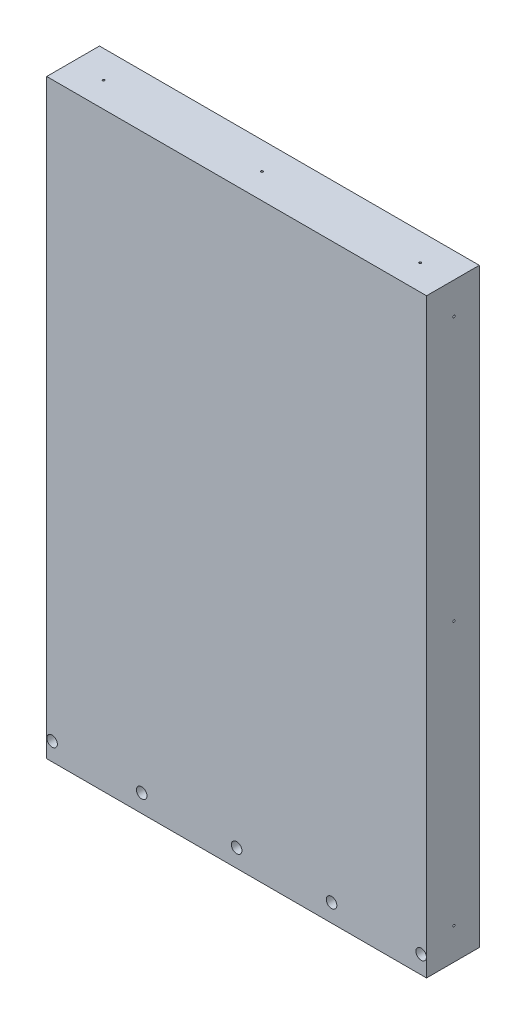
SolidWorks part; units mm, degrees
material "Cedro"
ref_plane "Plano frontal" through (0, 0, 0) normal (0, 0, 1) x (1, 0, 0)
ref_plane "Plano superior" through (0, 0, 0) normal (0, 1, 0) x (1, 0, 0)
ref_plane "Plano direito" through (0, 0, 0) normal (1, 0, 0) x (0, 0, -1)
sketch "Esboço1" plane through (0, 0, 0) normal (0, 0, 1) x (1, 0, 0)
  line L1 (0, 0) -> (180, 0)
  line L2 (0, 0) -> (0, 280)
  line L3 (0, 280) -> (180, 280)
  line L4 (180, 0) -> (180, 280)
  circle A0 centre (2.55, 8.5) radius 2.5
  circle A1 centre (45, 8.5) radius 2.5
  circle A2 centre (90, 8.5) radius 2.5
  circle A3 centre (135, 8.5) radius 2.5
  circle A4 centre (177.45, 8.5) radius 2.5
  dimension "D3" = 5
  dimension "D1" = 280
  dimension "D2" = 180
  dimension "D4" = 6
  dimension "D5" = 45
  dimension "D6" = 45
  dimension "D7" = 90
  dimension "D8" = 2.55
  dimension "D9" = 2.55
extrude "Ressalto-extrusão3" add sketch "Esboço1" along normal blind 25
sketch "Esboço2" plane through (0, 0, 0) normal (-1, 0, 0) x (0, 0, 1)
  line L0 (12, 280) -> (12, 0) construction
  line L1 (25, 280) -> (0, 280) construction
  line L2 (25, 0) -> (0, 0) construction
  point P6 (12, 15)
  point P7 (12, 140)
  point P8 (12, 265)
  dimension "D1" = 12
  dimension "D2" = 15
  dimension "D3" = 15
hole_wizard "Furo de diâmetro Ø1.0 (1)1" positions "3DSketch1" profile "Esboço3" hole size "Ø1.0" standard "Ansi Metric"
sketch3d "3DSketch1"
  point P0 (0, 265, 12)
  point P3 (0, 140, 12)
  point P6 (0, 15, 12)
  point P9 (0, 140, 12)
  point P11 (0, 15, 12)
  point P13 (0, 265, 12)
sketch "Esboço3" plane through (0, 265, 12) normal (0, 1, 0) x (0, 0, 1)
  line L0 (0, 0) -> (0, 10.3004)
  line L1 (0, 10.3004) -> (0.5, 10)
  line L2 (0.5, 10) -> (0.5, 0)
  line L5 (0.5, 0) -> (0, 0)
  line L10 (0, 10.3004) -> (-0.5, 10) construction
  line L11 (0, -6.35) -> (0, 107.95) construction
  dimension "Hole Dia." = 1
  dimension "Hole Depth" = 10
  dimension "Drill Angle" = 118
hole_wizard "Furo de diâmetro Ø1.0 (1)2" positions "Esboço5" profile "Esboço4" hole size "Ø1.0" standard "Ansi Metric"
sketch "Esboço5" plane through (180, 0, 0) normal (1, 0, 0) x (0, 0, -1)
  point P0 (-12, 15)
  point P3 (-12, 140)
  point P6 (-12, 265)
sketch "Esboço4" plane through (180, 15, 12) normal (0, 1, 0) x (0, 0, -1)
  line L0 (0, 0) -> (0, 10.3004)
  line L1 (0, 10.3004) -> (0.5, 10)
  line L2 (0.5, 10) -> (0.5, 0)
  line L5 (0.5, 0) -> (0, 0)
  line L10 (0, 10.3004) -> (-0.5, 10) construction
  line L11 (0, -6.35) -> (0, 107.95) construction
  dimension "Hole Dia." = 1
  dimension "Hole Depth" = 10
  dimension "Drill Angle" = 118
sketch "Esboço6" plane through (0, 0, 0) normal (0, -1, 0) x (-1, 0, 0)
  line L0 (0, -13) -> (-180, -13) construction
  line L1 (0, -25) -> (0, 0) construction
  line L2 (-180, -25) -> (-180, 0) construction
  line L3 (0, -25) -> (-180, -25) construction
  point P8 (-15, -13)
  point P9 (-90, -13)
  point P10 (-165, -13)
  dimension "D1" = 12
  dimension "D2" = 15
  dimension "D3" = 15
hole_wizard "Furo de diâmetro Ø1.0 (1)3" positions "3DSketch2" profile "Esboço7" hole size "Ø1.0" standard "Ansi Metric"
sketch3d "3DSketch2"
  point P0 (15, 0, 13)
  point P3 (90, 0, 13)
  point P6 (165, 0, 13)
sketch "Esboço7" plane through (15, 0, 13) normal (1, 0, 0) x (0, 0, -1)
  line L0 (0, 0) -> (0, 10.3004)
  line L1 (0, 10.3004) -> (0.5, 10)
  line L2 (0.5, 10) -> (0.5, 0)
  line L5 (0.5, 0) -> (0, 0)
  line L10 (0, 10.3004) -> (-0.5, 10) construction
  line L11 (0, -6.35) -> (0, 107.95) construction
  dimension "Hole Dia." = 1
  dimension "Hole Depth" = 10
  dimension "Drill Angle" = 118
hole_wizard "Furo de diâmetro Ø1.0 (1)4" positions "Esboço9" profile "Esboço8" hole size "Ø1.0" standard "Ansi Metric"
sketch "Esboço9" plane through (0, 280, 0) normal (0, 1, 0) x (1, 0, 0)
  point P0 (15, -13)
  point P3 (90, -13)
  point P6 (165, -13)
sketch "Esboço8" plane through (15, 280, 13) normal (1, 0, 0) x (0, 0, 1)
  line L0 (0, 0) -> (0, 10.3004)
  line L1 (0, 10.3004) -> (0.5, 10)
  line L2 (0.5, 10) -> (0.5, 0)
  line L5 (0.5, 0) -> (0, 0)
  line L10 (0, 10.3004) -> (-0.5, 10) construction
  line L11 (0, -6.35) -> (0, 107.95) construction
  dimension "Hole Dia." = 1
  dimension "Hole Depth" = 10
  dimension "Drill Angle" = 118
